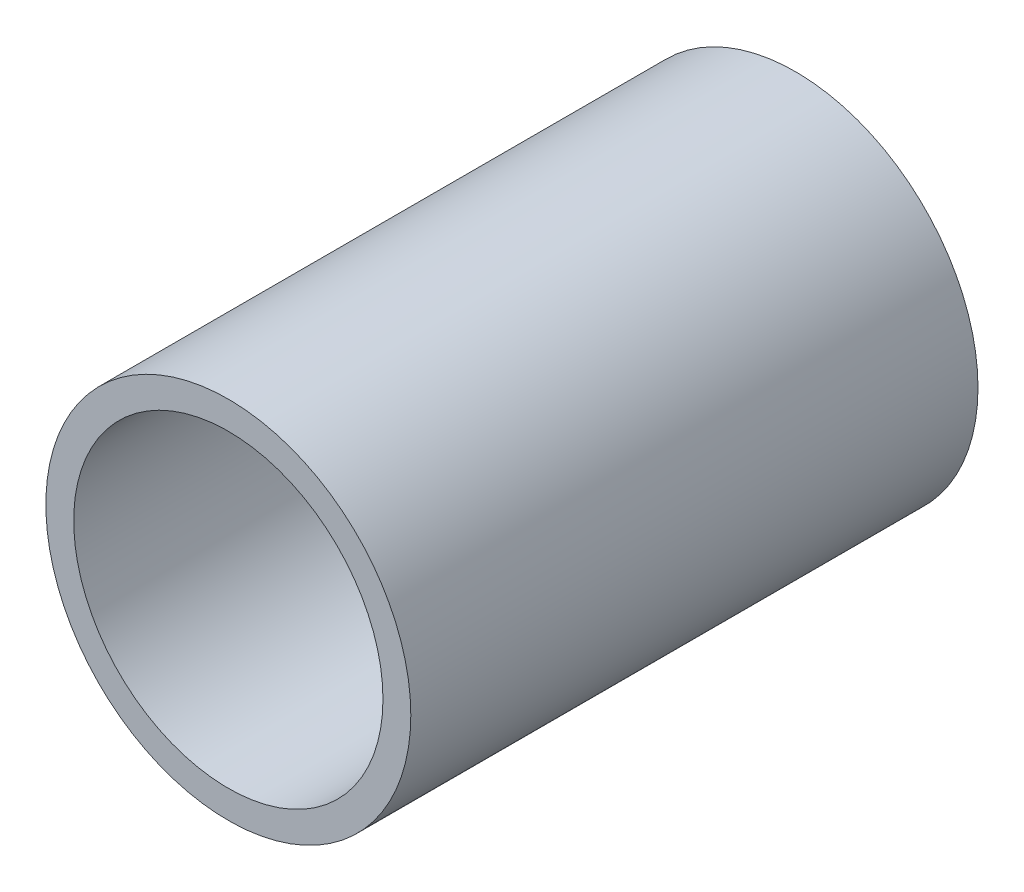
SolidWorks part; units mm, degrees
ref_plane "Alzado" through (0, 0, 0) normal (0, 0, 1) x (1, 0, 0)
ref_plane "Planta" through (0, 0, 0) normal (0, 1, 0) x (1, 0, 0)
ref_plane "Vista lateral" through (0, 0, 0) normal (1, 0, 0) x (0, 0, -1)
sketch "Croquis2" plane through (0, 0, 0) normal (0, 0, 1) x (1, 0, 0)
  circle A0 centre (0, 0) radius 24.13
  circle A1 centre (0, 0) radius 20.447
  dimension "D1" = 48.26
  dimension "D2" = 3.683
extrude "Saliente-Extruir1" add sketch "Croquis2" along normal mid plane 75
